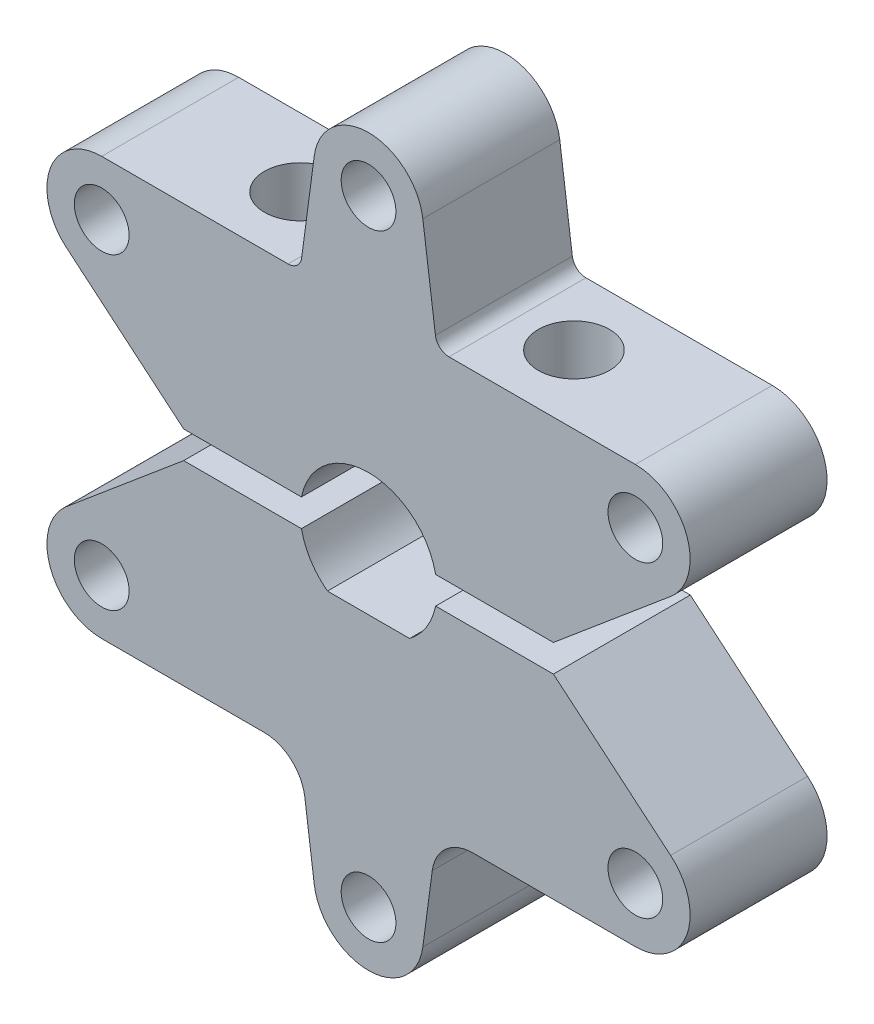
SolidWorks part; units mm, degrees
material "6061 合金"
ref_plane "前视基准面" through (0, 0, 0) normal (0, 0, 1) x (1, 0, 0)
ref_plane "上视基准面" through (0, 0, 0) normal (0, 1, 0) x (1, 0, 0)
ref_plane "右视基准面" through (0, 0, 0) normal (1, 0, 0) x (0, 0, -1)
sketch "草图1" plane through (0, 0, 0) normal (0, 0, 1) x (1, 0, 0)
  line L0 (-3, -4) -> (3, -4)
  line L6 (-19.4856, -15.25) -> (19.4856, -15.25)
  line L7 (-13.5, 1) -> (-4.899, 1)
  line L8 (0, 0) -> (0, -15.25) construction
  line L9 (-22.058, 8.1869) -> (-13.5, 1)
  line L10 (-22.058, -8.1869) -> (-13.5, -1)
  line L11 (-13.5, -1) -> (-4.899, -1)
  line L12 (13.5, -1) -> (22.058, -8.1869)
  line L13 (-22.5, 0) -> (22.5, 0) construction
  line L14 (-19.4856, 15.25) -> (19.4856, 15.25)
  line L15 (13.5, 1) -> (22.058, 8.1869)
  line L16 (4.899, 1) -> (13.5, 1)
  line L17 (4.899, -1) -> (13.5, -1)
  arc A0 (3, -4) -> (4.899, -1) centre (0, 0) ccw
  circle A1 centre (0, 0) radius 22.5 construction
  circle A2 centre (0, 22.5) radius 2 construction
  circle A3 centre (19.4856, 11.25) radius 2
  circle A4 centre (19.4856, -11.25) radius 2
  circle A5 centre (0, -22.5) radius 2 construction
  circle A6 centre (-19.4856, -11.25) radius 2
  circle A7 centre (-19.4856, 11.25) radius 2
  arc A10 (-22.058, -8.1869) -> (-19.4856, -15.25) centre (-19.4856, -11.25) ccw
  arc A12 (19.4856, -15.25) -> (22.058, -8.1869) centre (19.4856, -11.25) ccw
  arc A13 (-22.058, 8.1869) -> (-19.4856, 15.25) centre (-19.4856, 11.25) cw
  arc A14 (19.4856, 15.25) -> (22.058, 8.1869) centre (19.4856, 11.25) cw
  arc A15 (-4.899, -1) -> (-3, -4) centre (0, 0) ccw
  arc A16 (4.899, 1) -> (-4.899, 1) centre (0, 0) ccw
  point P19 (0, 0)
  dimension "D1" = 10
  dimension "D3" = 45
  dimension "D5" = 4
  dimension "D6" = 4
  dimension "D2" = 4
  dimension "D9" = 2
  dimension "D10" = 27
  dimension "D4" = 6
extrude "凸台-拉伸1" add sketch "草图1" along normal blind 10
sketch "草图3" plane through (0, 15.25, 0) normal (0, 1, 0) x (1, 0, 0)
  line L0 (10, -5) -> (-10, -5) construction
  line L1 (0, -10) -> (0, -5) construction
  line L2 (19.4856, -10) -> (-19.4856, -10) construction
  line L3 (0, -5) -> (0, 0) construction
  circle A0 centre (10, -5) radius 2.6
  circle A1 centre (-10, -5) radius 2.6
  dimension "D1" = 5.2
  dimension "D2" = 20
extrude "切除-拉伸2" cut sketch "草图3" against normal up to next (14.25 mm away) and the other way through all
sketch "草图4" plane through (0, 15.25, 0) normal (0, 1, 0) x (1, 0, 0)
  circle A0 centre (10, -5) radius 2
  circle A1 centre (-10, -5) radius 2
  dimension "D1" = 4
extrude "切除-拉伸3" cut sketch "草图4" against normal through all
cosmetic thread "装饰螺纹线5" parameters "D2"=5
cosmetic thread "装饰螺纹线6" parameters "D2"=5
sketch "草图5" plane through (0, 0, 0) normal (0, 0, -1) x (-1, 0, 0)
  line L0 (-3.965, -23.0276) -> (-5, -15.25)
  line L1 (19.4856, -15.25) -> (-19.4856, -15.25) construction
  line L2 (-5, -15.25) -> (5, -15.25)
  line L3 (5, -15.25) -> (3.965, -23.0276)
  line L4 (-22.5, 0) -> (22.5, 0) construction
  line L5 (5, 15.25) -> (3.965, 23.0276)
  line L6 (-5, 15.25) -> (5, 15.25)
  line L7 (-3.965, 23.0276) -> (-5, 15.25)
  circle A1 centre (0, -22.5) radius 2
  circle A3 centre (0, -22.5) radius 2 construction
  arc A5 (-3.965, -23.0276) -> (3.965, -23.0276) centre (0, -22.5) ccw
  arc A7 (19.4856, -15.25) -> (22.058, -8.1869) centre (19.4856, -11.25) ccw construction
  arc A8 (-3.965, 23.0276) -> (3.965, 23.0276) centre (0, 22.5) cw
  circle A9 centre (0, 22.5) radius 2
  dimension "D1" = 10
extrude "凸台-拉伸2" add sketch "草图5" against normal up to surface (10 mm away) up to face at (0, 7.0843, 10)
fillet "圆角1" radius 3 2 edges at (-5, -15.25, 5) (5, -15.25, 5)
fillet "圆角2" radius 1 2 edges at (-5, 15.25, 5) (5, 15.25, 5)
scale "缩放比例1" bodies to scale 123 124 scale about origin uniform scaling yes scale factor 0.8
scale "缩放比例2" bodies to scale 126 125 scale about origin uniform scaling yes scale factor 0.8
scale "缩放比例3" bodies to scale 128 127 scale about origin uniform scaling yes scale factor 0.8
